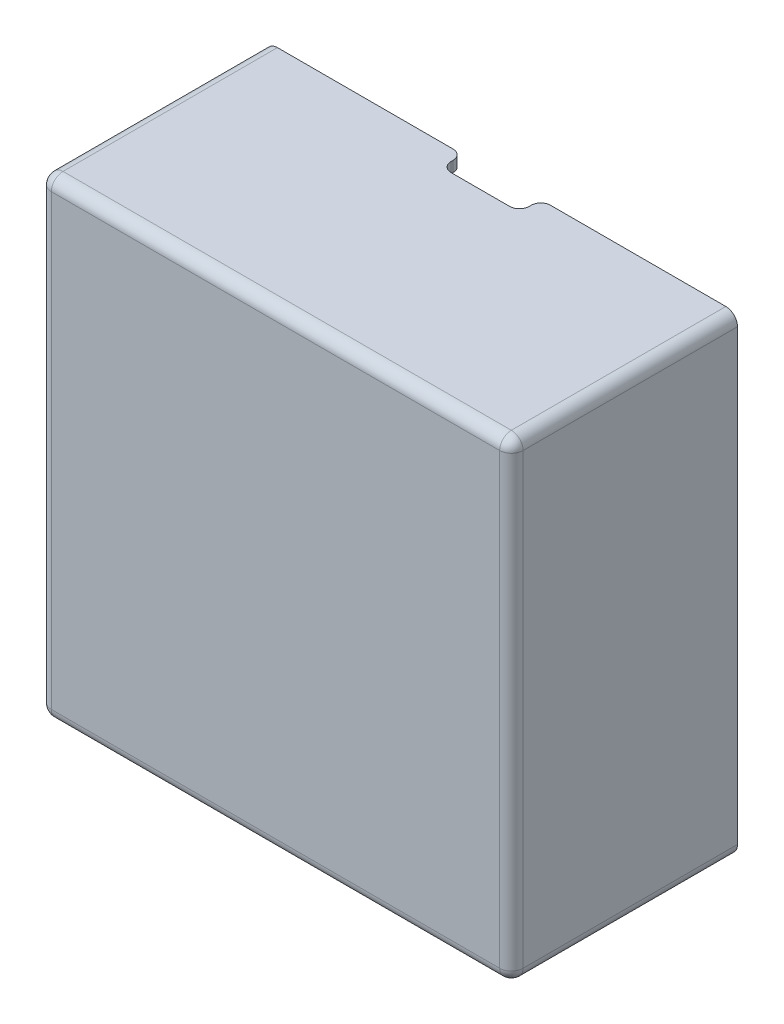
SolidWorks part; units mm, degrees
ref_plane "Front Plane" through (0, 0, 0) normal (0, 0, 1) x (1, 0, 0)
ref_plane "Top Plane" through (0, 0, 0) normal (0, 1, 0) x (1, 0, 0)
ref_plane "Right Plane" through (0, 0, 0) normal (1, 0, 0) x (0, 0, -1)
sketch "Sketch1" plane through (0, 0, 0) normal (0, 0, 1) x (1, 0, 0)
  line L1 (60.5, 60.5) -> (-60.5, 60.5)
  line L2 (60.5, 60.5) -> (60.5, -60.5)
  line L3 (60.5, -60.5) -> (-60.5, -60.5)
  line L4 (-60.5, 60.5) -> (-60.5, -60.5)
  line L5 (60.5, 60.5) -> (-60.5, -60.5) construction
  line L6 (60.5, -60.5) -> (-60.5, 60.5) construction
  line L7 (57.75, 57.75) -> (-57.75, 57.75)
  line L8 (57.75, 57.75) -> (57.75, -57.75)
  line L9 (57.75, -57.75) -> (-57.75, -57.75)
  line L10 (-57.75, 57.75) -> (-57.75, -57.75)
  line L11 (57.75, 57.75) -> (-57.75, -57.75) construction
  line L12 (57.75, -57.75) -> (-57.75, 57.75) construction
  point P0 (0, 0)
  point P6 (0, 0)
  dimension "D1" = 121
  dimension "D2" = 121
  dimension "D3" = 115.5
  dimension "D4" = 115.5
extrude "Boss-Extrude1" add sketch "Sketch1" along normal blind 55
sketch "Sketch2" plane through (0, 0, 55) normal (0, 0, 1) x (1, 0, 0)
  line L1 (60.5, -60.5) -> (-60.5, -60.5)
  line L2 (60.5, -60.5) -> (60.5, 60.5)
  line L3 (60.5, 60.5) -> (-60.5, 60.5)
  line L4 (-60.5, -60.5) -> (-60.5, 60.5)
  line L5 (60.5, -60.5) -> (-60.5, 60.5) construction
  line L6 (60.5, 60.5) -> (-60.5, -60.5) construction
  point P0 (0, 0)
extrude "Boss-Extrude2" add sketch "Sketch2" along normal blind 3
fillet "Fillet1" radius 3 8 edges at (0, -57.75, 55) (57.75, 0, 55) (0, 57.75, 55) (-57.75, 0, 55) (-57.75, 57.75, 27.5) (-57.75, -57.75, 27.5) (57.75, -57.75, 27.5) (57.75, 57.75, 27.5)
fillet "Fillet2" radius 3 8 edges at (0, 60.5, 58) (60.5, 0, 58) (0, -60.5, 58) (-60.5, 0, 58) (60.5, -60.5, 29) (-60.5, -60.5, 29) (-60.5, 60.5, 29) (60.5, 60.5, 29)
sketch "Sketch3" plane through (0, -60.5, 0) normal (0, -1, 0) x (1, 0, 0)
  line L1 (10.0543, -4.504) -> (-9.9457, -4.504)
  line L2 (10.0543, -4.504) -> (10.0543, 5.496)
  line L3 (10.0543, 5.496) -> (-9.9457, 5.496)
  line L4 (-9.9457, -4.504) -> (-9.9457, 5.496)
  line L5 (10.0543, -4.504) -> (-9.9457, 5.496) construction
  line L6 (10.0543, 5.496) -> (-9.9457, -4.504) construction
  dimension "D1" = 10
  dimension "D2" = 20
extrude "Cut-Extrude1" cut sketch "Sketch3" against normal blind 177
fillet "Fillet3" radius 2.5 4 edges at (-9.9457, -59.125, 5.496) (10.0543, -59.125, 5.496) (10.0543, -59.125, 0) (-9.9457, -59.125, 0)
fillet "Fillet4" radius 2.5 4 edges at (-9.9457, 59.125, 5.496) (-9.9457, 59.125, 0) (10.0543, 59.125, 5.496) (10.0543, 59.125, 0)
